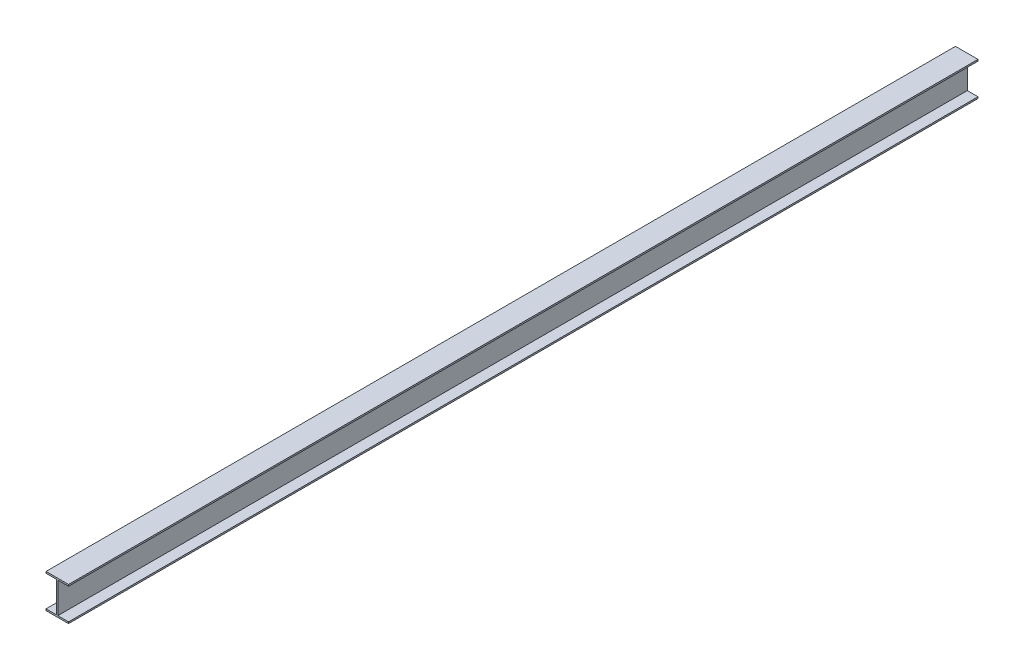
SolidWorks part; units mm, degrees
material "ASTM A992 Steel"
ref_plane "Front" through (0, 0, 0) normal (0, 0, 1) x (1, 0, 0)
ref_plane "Top" through (0, 0, 0) normal (0, 1, 0) x (1, 0, 0)
ref_plane "Right" through (0, 0, 0) normal (1, 0, 0) x (0, 0, -1)
sketch "Sketch1" plane through (0, 0, 0) normal (0, 0, 1) x (1, 0, 0)
  line L0 (0, -0.0002) -> (101.6, -0.0002)
  line L1 (101.6, -0.0002) -> (101.6, -7.1122)
  line L2 (101.6, -7.1122) -> (53.408, -7.1122)
  line L3 (53.408, -7.1122) -> (53.408, -146.0502)
  line L4 (53.408, -146.0502) -> (101.6, -146.0502)
  line L5 (101.6, -146.0502) -> (101.6, -153.1622)
  line L6 (101.6, -153.1622) -> (0, -153.1622)
  line L7 (0, -153.1622) -> (0, -146.0502)
  line L8 (0, -146.0502) -> (47.566, -146.0502)
  line L9 (47.566, -146.0502) -> (47.566, -7.1122)
  line L10 (47.566, -7.1122) -> (0, -7.1122)
  line L11 (0, -7.1122) -> (0, -0.0002)
  line L12 (50.8, -0.0002) -> (50.8, -153.1622) construction
  dimension "D1" = 5.842
  dimension "D2" = 7.112
  dimension "D3" = 7.112
  dimension "D4" = 7.112
  dimension "D5" = 153.162
  dimension "D6" = 50.8
  dimension "D7" = 50.8
  dimension "D8" = 47.566
extrude "Boss-Extrude1" add sketch "Sketch1" along normal blind 4100
sketch "Sketch2" plane through (0, -153.1622, 0) normal (0, -1, 0) x (1, 0, 0)
  line L2 (101.6, 4100) -> (101.6, 0) construction
  line L5 (101.6, 2050) -> (101.6, 2202.4)
  line L6 (101.6, 2202.4) -> (-229.7319, 2202.4)
  line L7 (-229.7319, 2000) -> (-229.7319, 2202.4)
  line L9 (101.6, 2050) -> (101.6, 1897.6)
  line L10 (101.6, 1897.6) -> (-229.7319, 1897.6)
  line L11 (-229.7319, 2000) -> (-229.7319, 1897.6)
  point P0 (101.6, 2050)
  dimension "D1" = 152.4
  dimension "D2" = 152.4
split line "Split Line1"
